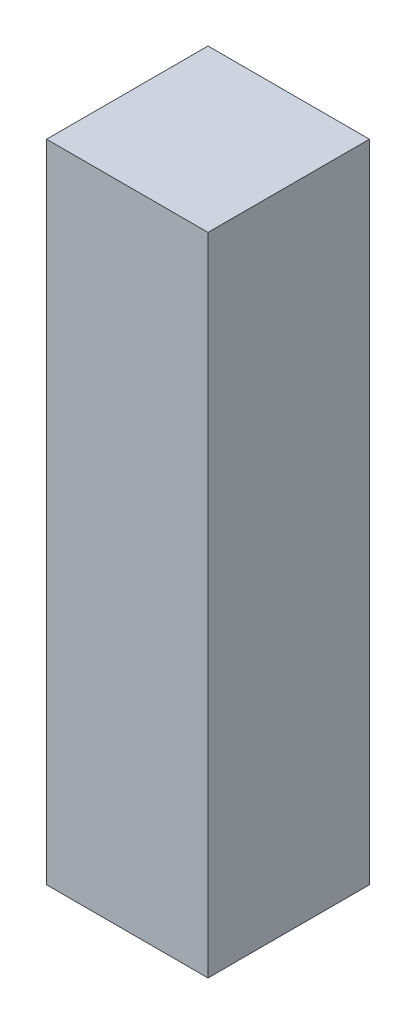
SolidWorks part; units mm, degrees
material "Mahogany"
ref_plane "Front Plane" through (0, 0, 0) normal (0, 0, 1) x (1, 0, 0)
ref_plane "Top Plane" through (0, 0, 0) normal (0, 1, 0) x (1, 0, 0)
ref_plane "Right Plane" through (0, 0, 0) normal (1, 0, 0) x (0, 0, -1)
sketch "Sketch1" plane through (0, 0, 0) normal (0, 1, 0) x (1, 0, 0)
  line L1 (-2.5, 2.5) -> (2.5, 2.5)
  line L2 (-2.5, 2.5) -> (-2.5, -2.5)
  line L3 (-2.5, -2.5) -> (2.5, -2.5)
  line L4 (2.5, 2.5) -> (2.5, -2.5)
  line L5 (-2.5, 2.5) -> (2.5, -2.5) construction
  line L6 (-2.5, -2.5) -> (2.5, 2.5) construction
  point P0 (0, 0)
  dimension "D1" = 5
  dimension "D2" = 5
extrude "Boss-Extrude1" add sketch "Sketch1" along normal blind 20
